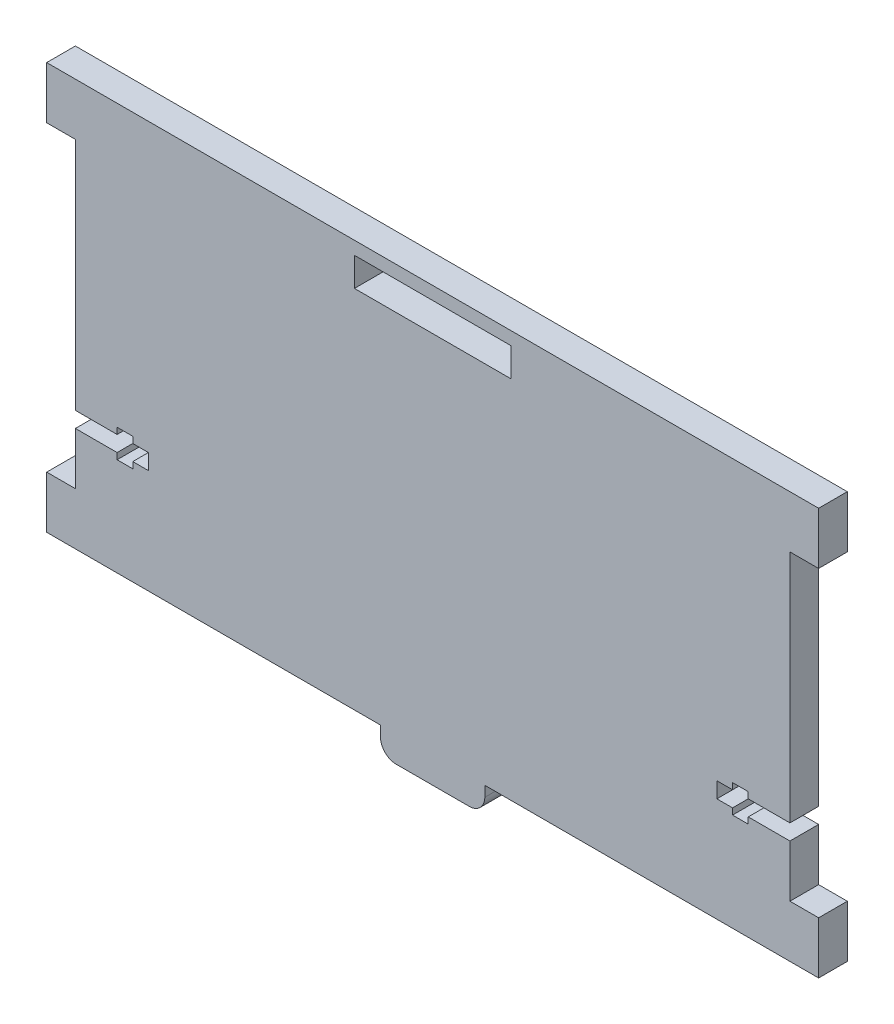
SolidWorks part; units mm, degrees
ref_plane "Front Plane" through (0, 0, 0) normal (0, 0, 1) x (1, 0, 0)
ref_plane "Top Plane" through (0, 0, 0) normal (0, 1, 0) x (1, 0, 0)
ref_plane "Right Plane" through (0, 0, 0) normal (1, 0, 0) x (0, 0, -1)
sketch "Sketch1" plane through (0, 0, 0) normal (0, 0, 1) x (1, 0, 0)
  line L0 (78.5, 0) -> (137, 0)
  line L1 (0, 0) -> (58.5, 0)
  line L2 (0, 10) -> (0, 20)
  line L3 (0, 78) -> (137, 78)
  line L4 (137, 10) -> (137, 20)
  line L5 (53.5, 75.5) -> (83.5, 75.5)
  line L6 (53.5, 75.5) -> (53.5, 70)
  line L7 (53.5, 70) -> (83.5, 70)
  line L8 (83.5, 75.5) -> (83.5, 70)
  line L9 (0, 78) -> (-5.5, 78)
  line L10 (137, 23) -> (137, 68)
  line L11 (0, 68) -> (-5.5, 68)
  line L12 (-5.5, 78) -> (-5.5, 68)
  line L13 (0, 0) -> (-5.5, 0)
  line L14 (58.5, 0) -> (58.5, -5)
  line L15 (0, 10) -> (-5.5, 10)
  line L16 (-5.5, 0) -> (-5.5, 10)
  line L17 (137, 78) -> (142.5, 78)
  line L18 (58.5, -5) -> (78.5, -5)
  line L19 (137, 68) -> (142.5, 68)
  line L20 (142.5, 78) -> (142.5, 68)
  line L21 (137, 0) -> (142.5, 0)
  line L22 (78.5, 0) -> (78.5, -5)
  line L23 (137, 10) -> (142.5, 10)
  line L24 (142.5, 0) -> (142.5, 10)
  line L25 (137, 23) -> (129, 23)
  line L26 (0, 23) -> (0, 68)
  line L27 (137, 20) -> (129, 20)
  line L28 (123, 23) -> (123, 20)
  line L29 (126, 24.2) -> (129, 24.2)
  line L30 (126, 24.2) -> (126, 23)
  line L31 (126, 18.8) -> (129, 18.8)
  line L32 (129, 24.2) -> (129, 23)
  line L33 (129, 20) -> (129, 18.8)
  line L34 (126, 20) -> (126, 18.8)
  line L35 (126, 20) -> (123, 20)
  line L36 (126, 23) -> (123, 23)
  line L37 (8, 24.2) -> (11, 24.2)
  line L38 (0, 23) -> (8, 23)
  line L39 (11, 20) -> (14, 20)
  line L40 (0, 20) -> (8, 20)
  line L41 (14, 23) -> (14, 20)
  line L42 (8, 24.2) -> (8, 23)
  line L43 (8, 18.8) -> (11, 18.8)
  line L44 (11, 24.2) -> (11, 23)
  line L45 (8, 20) -> (8, 18.8)
  line L46 (11, 20) -> (11, 18.8)
  line L47 (11, 23) -> (14, 23)
  dimension "D1" = 137
  dimension "D2" = 78
  dimension "D3" = 30
  dimension "D4" = 2.5
  dimension "D5" = 5.5
  dimension "D6" = 53.5
  dimension "D7" = 5.5
  dimension "D8" = 5.5
  dimension "D9" = 10
  dimension "D10" = 10
  dimension "D11" = 10
  dimension "D12" = 10
  dimension "D13" = 5.5
  dimension "D14" = 5.5
  dimension "D15" = 5
  dimension "D16" = 20
  dimension "D17" = 5
  dimension "D18" = 3
  dimension "D19" = 10
  dimension "D20" = 14
  dimension "D21" = 8
  dimension "D22" = 3
  dimension "D23" = 1.2
  dimension "D24" = 5.4
  dimension "D25" = 10
  dimension "D26" = 3
  dimension "D27" = 14
  dimension "D28" = 3
  dimension "D29" = 8
  dimension "D30" = 1.2
  dimension "D31" = 5.4
extrude "Boss-Extrude2" add sketch "Sketch1" along normal blind 5.5
fillet "Fillet1" radius 3 1 edges at (78.5, -5, 2.75)
fillet "Fillet2" radius 3 1 edges at (58.5, -5, 2.75)
